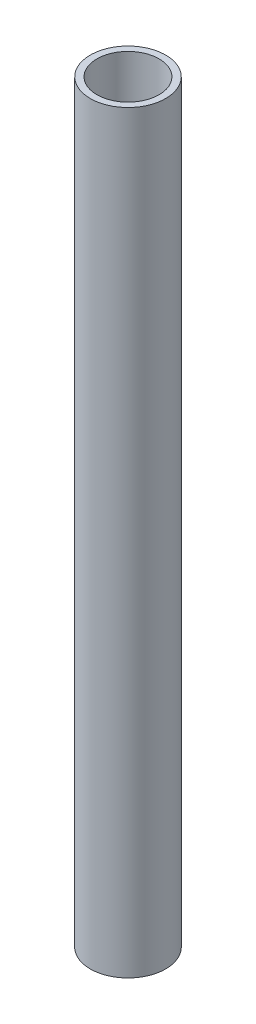
SolidWorks part; units mm, degrees
material "AISI 304"
ref_plane "Front Plane" through (0, 0, 0) normal (0, 0, 1) x (1, 0, 0)
ref_plane "Top Plane" through (0, 0, 0) normal (0, 1, 0) x (1, 0, 0)
ref_plane "Right Plane" through (0, 0, 0) normal (1, 0, 0) x (0, 0, -1)
sketch "Sketch2" plane through (0, 0, 0) normal (0, 1, 0) x (1, 0, 0)
  circle A0 centre (0, 0) radius 2
  dimension "D1" = 4
extrude "Boss-Extrude1" add sketch "Sketch2" along normal mid plane 40
sketch "Sketch3" plane through (0, 20, 0) normal (0, 1, 0) x (1, 0, 0)
  circle A0 centre (0, 0) radius 1.65
  dimension "D1" = 3.3
extrude "Cut-Extrude1" cut sketch "Sketch3" against normal through all both and the other way through all
